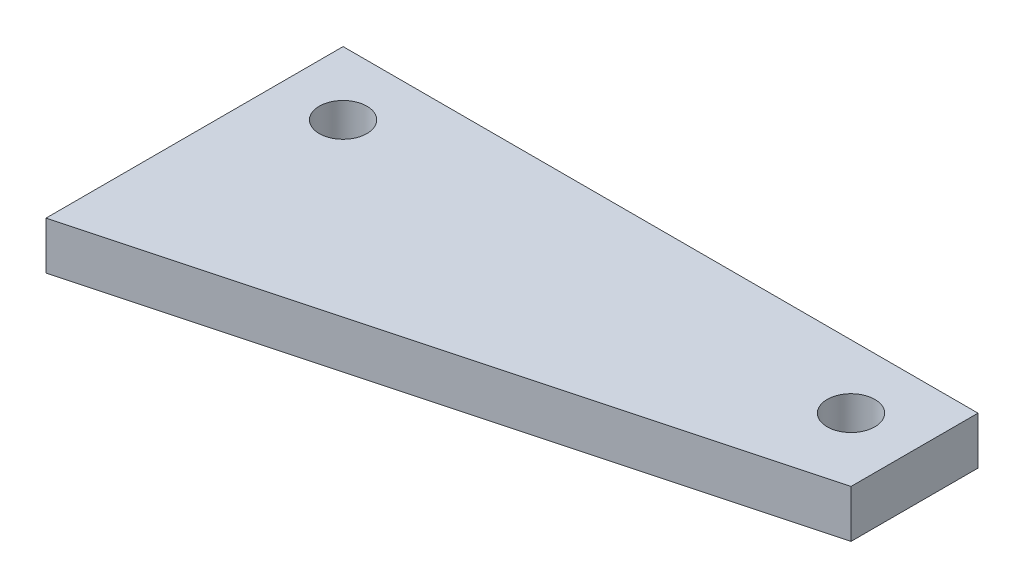
SolidWorks part; units mm, degrees
ref_plane "Front Plane" through (0, 0, 0) normal (0, 0, 1) x (1, 0, 0)
ref_plane "Top Plane" through (0, 0, 0) normal (0, 1, 0) x (1, 0, 0)
ref_plane "Right Plane" through (0, 0, 0) normal (1, 0, 0) x (0, 0, -1)
sketch "Sketch1" plane through (0, 0, 0) normal (0, 1, 0) x (1, 0, 0)
  line L2 (-31.75, -6.35) -> (-31.75, 6.35)
  line L3 (-31.75, 6.35) -> (31.75, 6.35)
  line L4 (31.75, -6.35) -> (31.75, 6.35)
  line L5 (-31.75, -6.35) -> (31.75, 6.35) construction
  line L6 (-31.75, 6.35) -> (31.75, -6.35) construction
  line L8 (-31.75, -6.35) -> (-31.75, -23.3648)
  line L9 (-31.75, -23.3648) -> (31.75, -6.35)
  line L10 (-31.75, -6.35) -> (31.75, -6.35) construction
  circle A0 centre (-25.4, 0) radius 2.3813
  circle A1 centre (25.4, 0) radius 2.3813
  point P0 (0, 0)
  point P11 (-31.75, 0)
  point P13 (31.75, 0)
  dimension "D5" = 4.7625
  dimension "D6" = 4.7625
  dimension "D1" = 63.5
  dimension "D2" = 12.7
  dimension "D3" = 6.35
  dimension "D4" = 6.35
  dimension "D7" = 105
extrude "Boss-Extrude1" add sketch "Sketch1" along normal blind 4.7625
